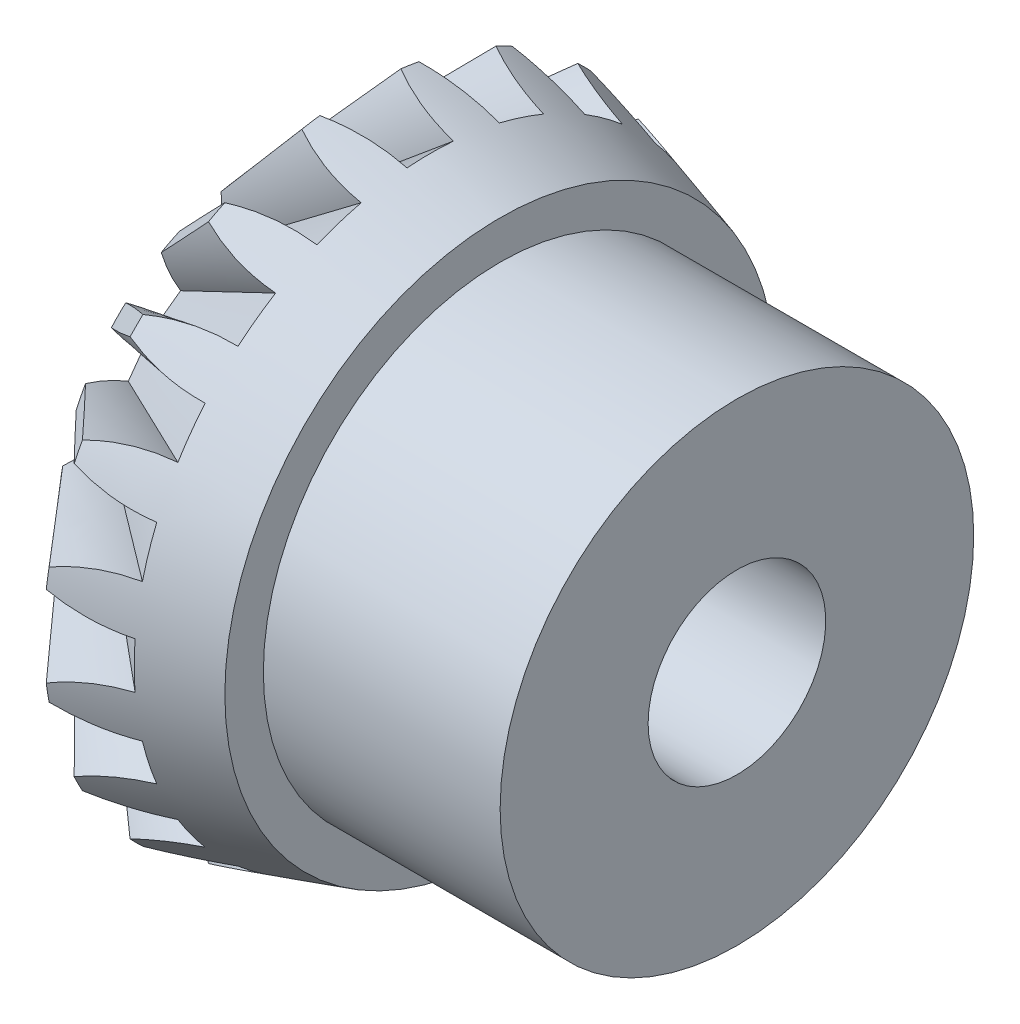
SolidWorks part; units mm, degrees
ref_plane "Front" through (0, 0, 0) normal (0, 0, 1) x (1, 0, 0)
ref_plane "Top" through (0, 0, 0) normal (0, 1, 0) x (1, 0, 0)
ref_plane "Right" through (0, 0, 0) normal (1, 0, 0) x (0, 0, -1)
sketch "Sketch1" plane through (0, 0, 0) normal (0, 0, 1) x (1, 0, 0)
  line L0 (0, 0) -> (8, 0) construction
  line L1 (0, 1.5) -> (8, 1.5)
  line L2 (8, 1.5) -> (8, 4)
  line L3 (8, 4) -> (4, 4)
  line L4 (4, 4) -> (4, 4.65)
  line L5 (4, 4.65) -> (1.6397, 5.35)
  line L6 (1.6397, 5.35) -> (0, 3.4628)
  line L7 (0, 3.4628) -> (0, 1.5)
  line L8 (2.8199, 5) -> (0, 1.7546) construction
  dimension "D1" = 49.013
  dimension "Overall Length" = 8
  dimension "OD" = 10.7
  dimension "For Shaft" = 3
  dimension "Face Width" = 2.5
  dimension "Hub Dia" = 8
  dimension "Hub Width" = 4
  dimension "PD" = 10
revolve "Revolve1" add sketch "Sketch1" angle 360 about L0
sketch "Sketch2" plane through (0, 0, 0) normal (-1, 0, 0) x (0, 0, 1)
  circle A0 centre (0, 0) radius 5
  dimension "Pitch Dia" = 10
sketch "Sketch3" plane through (0, 0, 0) normal (-1, 0, 0) x (0, 0, 1)
  line L0 (-10, 0) -> (10, 0) construction
  point P2 (0, 0)
  dimension "teeth" = 20
sketch "Sketch5" plane through (0, 0, 0) normal (-1, 0, 0) x (0, 0, 1)
  line L0 (0, 0) -> (0, 5.35) construction
  line L1 (0, 0) -> (0.4198, 5.3335) construction
  line L2 (0, 0) -> (-0.4198, 5.3335) construction
  line L4 (-10, 0) -> (10, 0) construction
  line L5 (-0.2099, 2.6668) -> (0.2099, 2.6668)
  line L6 (0, 0) -> (-1.6532, 5.0882) construction
  line L7 (0, 0) -> (1.6532, 5.0882) construction
  circle A0 centre (0, 0) radius 5.35 construction
  arc A1 (-0.2099, 2.6668) -> (-1.6532, 5.0882) centre (-3.3814, 2.4172) ccw
  arc A2 (0.2099, 2.6668) -> (1.6532, 5.0882) centre (3.3814, 2.4172) cw
  arc A3 (-1.6532, 5.0882) -> (1.6532, 5.0882) centre (0, 0) cw
  point P10 (0, 0)
  dimension "D1" = 9
  dimension "D2" = 36
ref_plane "Plane1" through (2.8199, 0, 0) normal (1, 0, 0) x (0, 0, -1)
sketch "Sketch6" plane through (2.8199, 0, 0) normal (1, 0, 0) x (0, 0, -1)
  line L0 (0, 0) -> (0, 8.025) construction
  line L1 (0, 0) -> (0.4198, 5.3335) construction
  line L2 (0, 0) -> (-0.4198, 5.3335) construction
  line L3 (0, 0) -> (2.6075, 8.025) construction
  line L4 (0, 0) -> (-2.6075, 8.025) construction
  line L5 (2.6075, 8.025) -> (-2.6075, 8.025) construction
  line L6 (0, 5.35) -> (0, 0) construction
  line L7 (-2.6075, 8.025) -> (2.6075, 8.025)
  circle A0 centre (0, 0) radius 5.35 construction
  arc A1 (-0.3923, 4.9846) -> (-2.6075, 8.025) centre (-3.9732, 4.7028) ccw
  arc A2 (0.3923, 4.9846) -> (2.6075, 8.025) centre (3.9732, 4.7028) cw
  circle A3 centre (0, 0) radius 5 construction
  arc A4 (0.3923, 4.9846) -> (-0.3923, 4.9846) centre (0, 0) ccw
  dimension "D1" = 9
  dimension "D2" = 36
  dimension "D3" = 8.025
  dimension "D4" = 5.35
loft "Cut-Loft1" cut profiles "Sketch6", "Sketch5"
pattern_circular "CirPattern1" count 20 over 360 about axis through (0, 0, 0) along (-1, 0, 0) of "Cut-Loft1"
sketch "Sketch7" plane through (0, 0, 0) normal (-1, 0, 0) x (0, 0, 1)
  circle A0 centre (0, 0) radius 5
sketch "Sketch8"
  dimension "D1" = 11
sketch_block_instance "Block1-1"
sketch_block "Block1"
equation "\"D1@Sketch5\"=(360deg/20)/2"
equation "\"D2@Sketch5\"=(360deg/20)/.5"
equation "\"D1@Sketch6\"=(360deg/\"teeth@Sketch5\")/2"
equation "\"D2@Sketch6\"=(360deg/\"teeth@Sketch5\")/.5"
equation "\"D3@Sketch6\"=\"D4@Sketch6\"*1.5"
equation "\"D1@Sketch8\"=\"Mounting Distance@Sketch8\""
